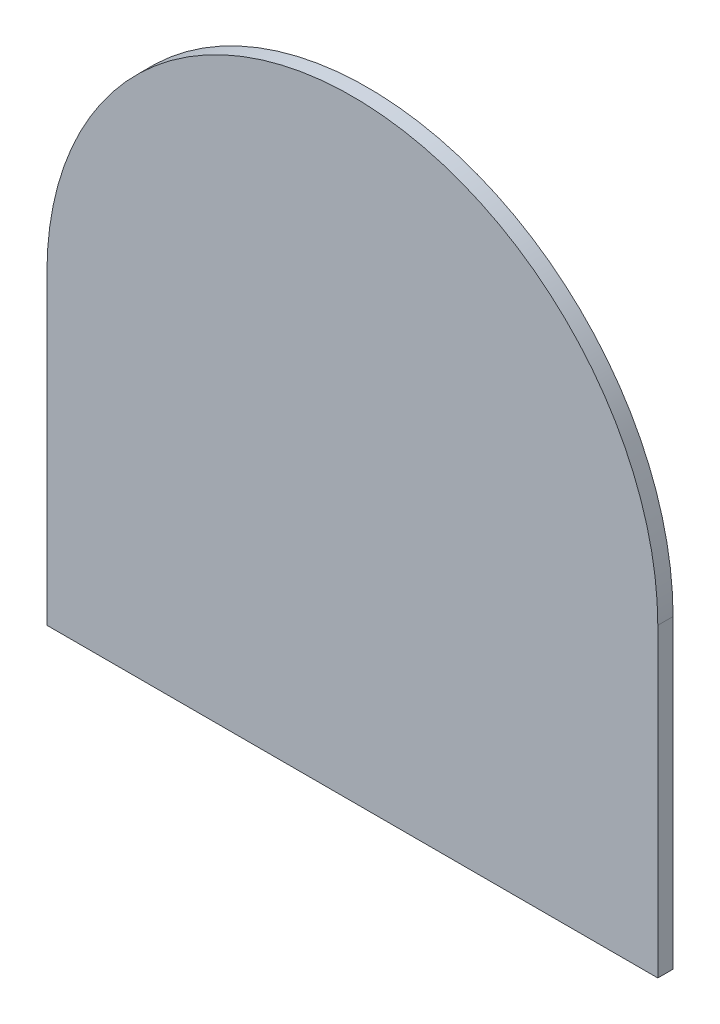
SolidWorks part; units mm, degrees
ref_plane "Front Plane" through (0, 0, 0) normal (0, 0, 1) x (1, 0, 0)
ref_plane "Top Plane" through (0, 0, 0) normal (0, 1, 0) x (1, 0, 0)
ref_plane "Right Plane" through (0, 0, 0) normal (1, 0, 0) x (0, 0, -1)
sketch "Sketch1" plane through (0, 0, 0) normal (0, 0, 1) x (1, 0, 0)
  line L1 (0, 0) -> (127, 0)
  line L2 (0, 0) -> (0, 63.5)
  line L4 (127, 0) -> (127, 63.5)
  arc A0 (127, 63.5) -> (0, 63.5) centre (63.5, 63.5) ccw
  dimension "D1" = 127
  dimension "D2" = 63.5
extrude "Extrude1" add sketch "Sketch1" against normal blind 3.175
sketch "Sketch2" plane through (0, 0, 0) normal (0, 0, 1) x (1, 0, 0)
  line L1 (18.9204, 86.8635) -> (18.9204, 34.4674)
  line L2 (93.5958, 86.8635) -> (108.0796, 86.8635)
  line L4 (108.0796, 86.8635) -> (108.0796, 34.4674)
  line L5 (108.0796, 34.4674) -> (93.5958, 34.4674)
  line L6 (18.9204, 34.4674) -> (33.4042, 34.4674)
  line L7 (33.4042, 86.8635) -> (18.9204, 86.8635)
  arc A0 (93.5958, 34.4674) -> (33.4042, 34.4674) centre (63.5, 57.8309) cw
  arc A2 (93.5958, 86.8635) -> (33.4042, 86.8635) centre (63.5, 63.5) ccw
